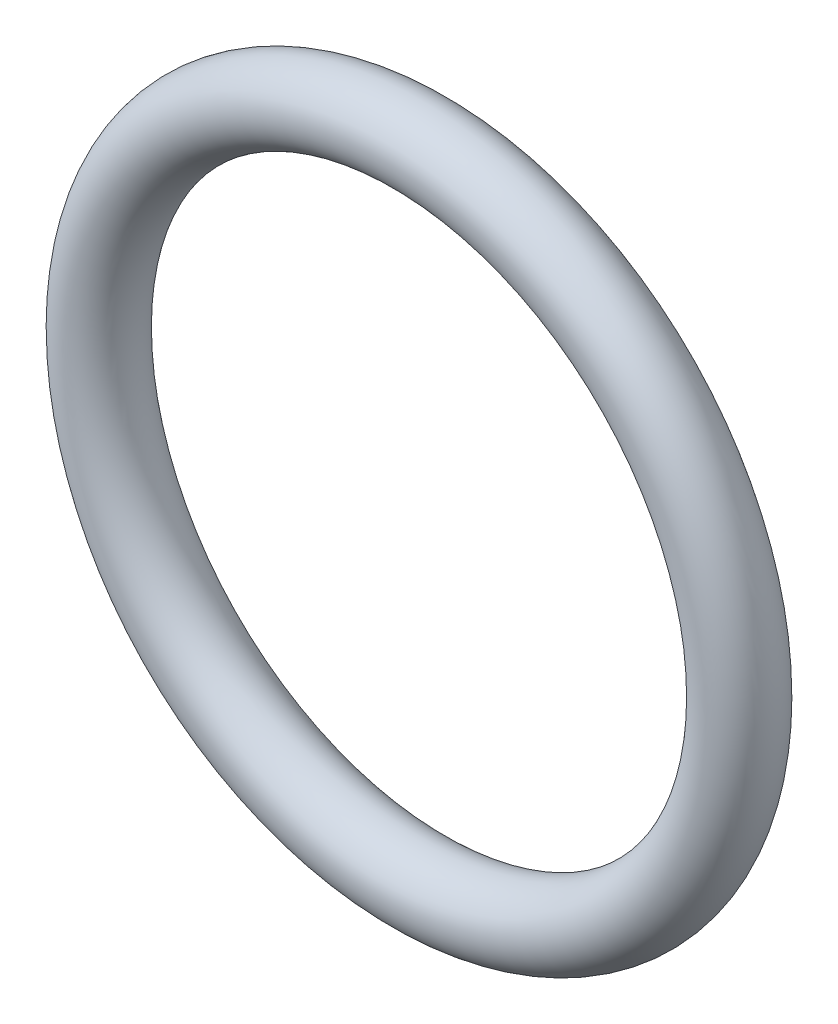
SolidWorks part; units mm, degrees
material "Резина"
ref_plane "Спереди" through (0, 0, 0) normal (0, 0, 1) x (1, 0, 0)
ref_plane "Сверху" through (0, 0, 0) normal (0, 1, 0) x (1, 0, 0)
ref_plane "Справа" through (0, 0, 0) normal (1, 0, 0) x (0, 0, -1)
sketch "Эскиз1" plane through (0, 0, 0) normal (0, 1, 0) x (1, 0, 0)
  line L0 (0, 0) -> (0, 5.3333) construction
  circle A0 centre (10.75, 0) radius 1.25
  point P2 (12, 0)
  dimension "D1" = 2.5
  dimension "D2" = 24
revolve "Повернуть1" add sketch "Эскиз1" angle 360 about L0
